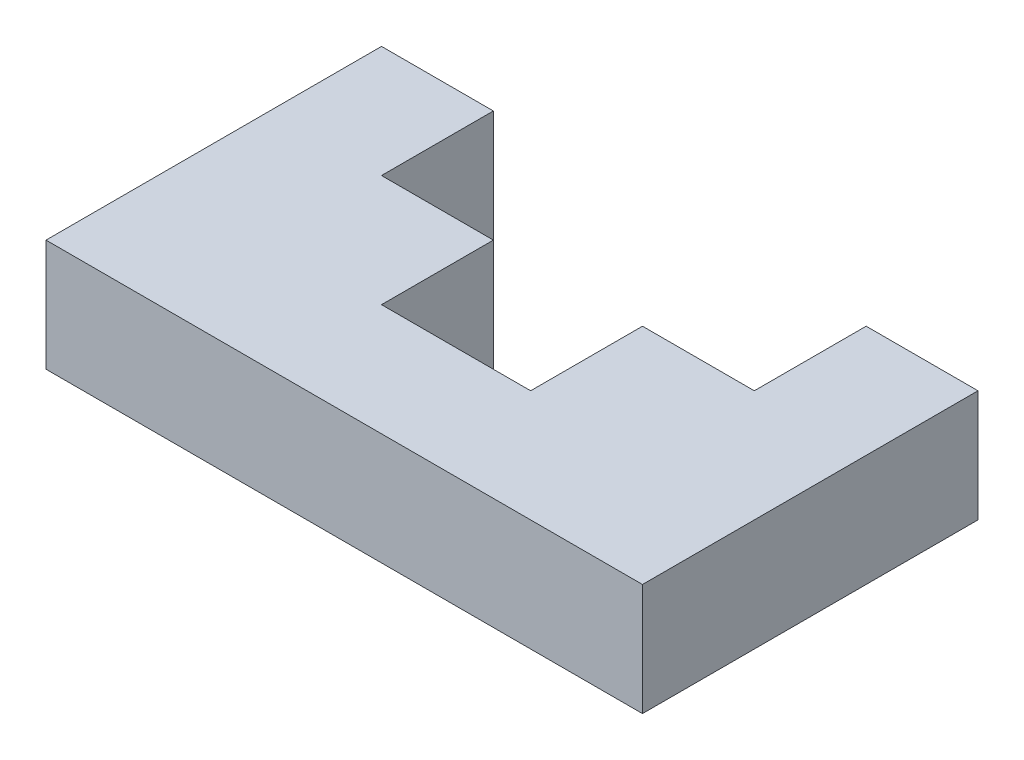
SolidWorks part; units mm, degrees
ref_plane "前视基准面" through (0, 0, 0) normal (0, 0, 1) x (1, 0, 0)
ref_plane "上视基准面" through (0, 0, 0) normal (0, 1, 0) x (1, 0, 0)
ref_plane "右视基准面" through (0, 0, 0) normal (1, 0, 0) x (0, 0, -1)
sketch "草图1" plane through (0, 0, 0) normal (0, 1, 0) x (1, 0, 0)
  line L0 (8, 0) -> (8, -9)
  line L1 (-5, -3) -> (-5, 0)
  line L2 (-5, 0) -> (-8, 0)
  line L3 (0, 0) -> (0, -6) construction
  line L4 (2, -3) -> (2, -6)
  line L5 (-2, -3) -> (-5, -3)
  line L6 (2, -3) -> (5, -3)
  line L7 (5, 0) -> (8, 0)
  line L8 (-2, -3) -> (-2, -6)
  line L9 (5, -3) -> (5, 0)
  line L10 (-8, 0) -> (-8, -9)
  line L11 (-8, -9) -> (8, -9)
  line L12 (-2, -6) -> (2, -6)
  point P4 (0, 0)
  point P9 (0, -9)
  dimension "D3" = 6
  dimension "D1" = 3
  dimension "D2" = 9
  dimension "D5" = 3
extrude "凸台-拉伸2" add sketch "草图1" along normal mid plane 3
